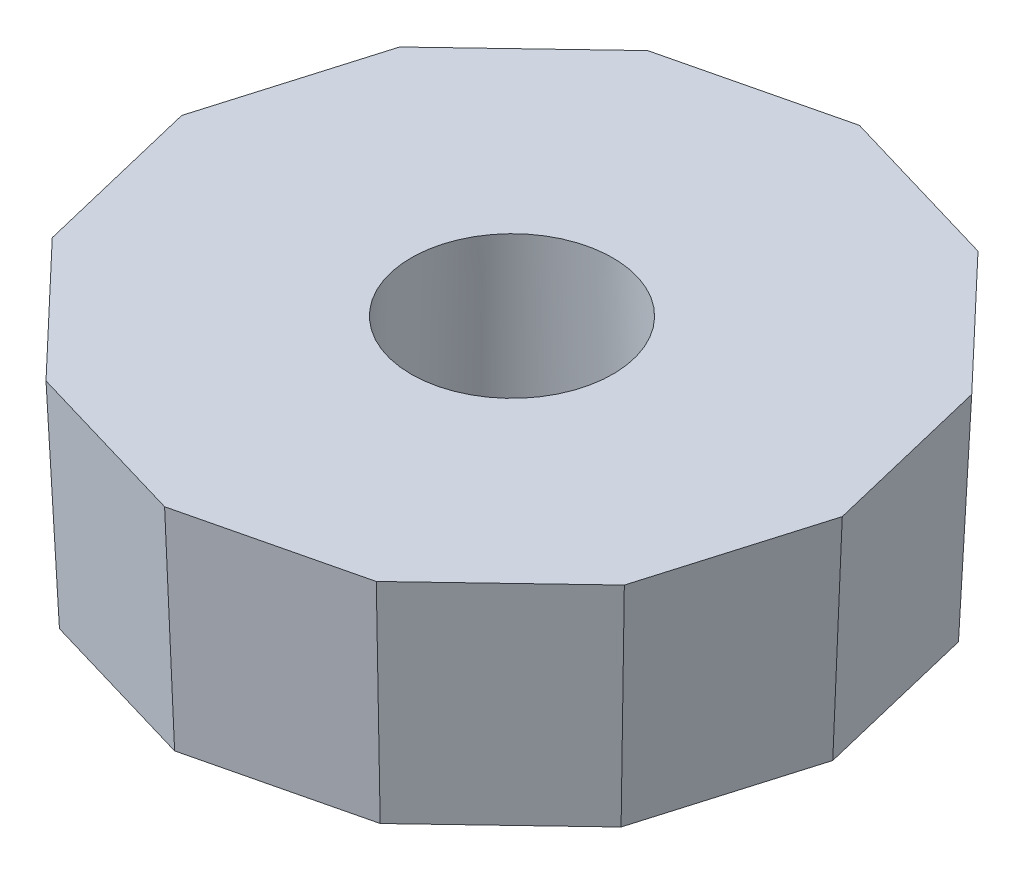
SolidWorks part; units mm, degrees
ref_plane "Front Plane" through (0, 0, 0) normal (0, 0, 1) x (1, 0, 0)
ref_plane "Top Plane" through (0, 0, 0) normal (0, 1, 0) x (1, 0, 0)
ref_plane "Right Plane" through (0, 0, 0) normal (1, 0, 0) x (0, 0, -1)
sketch "Sketch1" plane through (0, 0, 0) normal (0, 1, 0) x (1, 0, 0)
  line L1 (8.2456, -5.0426) -> (9.6622, -0.2442)
  line L2 (9.6622, -0.2442) -> (8.4898, 4.6196)
  line L3 (8.4898, 4.6196) -> (5.0426, 8.2456)
  line L4 (5.0426, 8.2456) -> (0.2442, 9.6622)
  line L5 (0.2442, 9.6622) -> (-4.6196, 8.4898)
  line L6 (-4.6196, 8.4898) -> (-8.2456, 5.0426)
  line L7 (-8.2456, 5.0426) -> (-9.6622, 0.2442)
  line L8 (-9.6622, 0.2442) -> (-8.4898, -4.6196)
  line L9 (-8.4898, -4.6196) -> (-5.0426, -8.2456)
  line L10 (-5.0426, -8.2456) -> (-0.2442, -9.6622)
  line L11 (-0.2442, -9.6622) -> (4.6196, -8.4898)
  line L12 (4.6196, -8.4898) -> (8.2456, -5.0426)
  circle A0 centre (0, 0) radius 9.336 construction
  circle A1 centre (0, 0) radius 3.2385
  dimension "D1" = 6.477
extrude "Boss-Extrude1" add sketch "Sketch1" along normal blind 6.35 draft 2.5 draft outward yes
